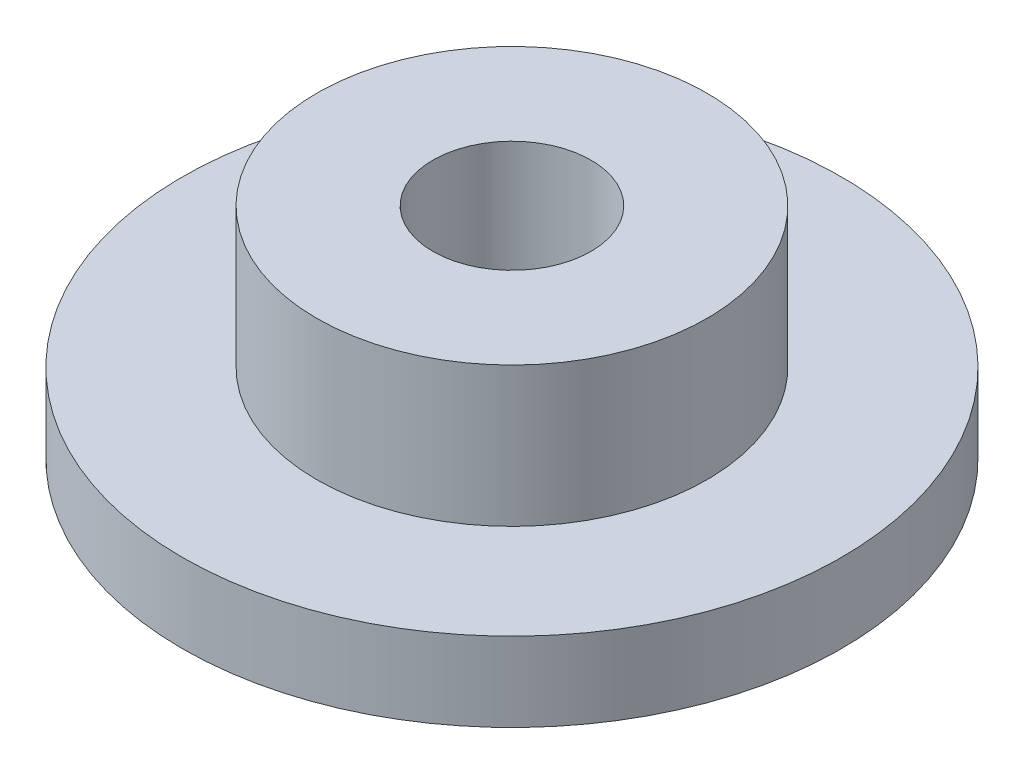
SolidWorks part; units mm, degrees
ref_plane "前视基准面" through (0, 0, 0) normal (0, 0, 1) x (1, 0, 0)
ref_plane "上视基准面" through (0, 0, 0) normal (0, 1, 0) x (1, 0, 0)
ref_plane "右视基准面" through (0, 0, 0) normal (1, 0, 0) x (0, 0, -1)
sketch "草图1" plane through (0, 0, 0) normal (0, 1, 0) x (1, 0, 0)
  circle A0 centre (0, 0) radius 12.5
  dimension "D1" = 25
extrude "凸台-拉伸1" add sketch "草图1" along normal blind 3
sketch "草图2" plane through (0, 3, 0) normal (0, 1, 0) x (1, 0, 0)
  circle A0 centre (0, 0) radius 7.4
  dimension "D1" = 14.8
extrude "凸台-拉伸2" add sketch "草图2" along normal blind 5.3
sketch "草图3" plane through (0, 8.3, 0) normal (0, 1, 0) x (1, 0, 0)
  circle A0 centre (0, 0) radius 3
  dimension "D1" = 6
extrude "切除-拉伸1" cut sketch "草图3" against normal up to next
